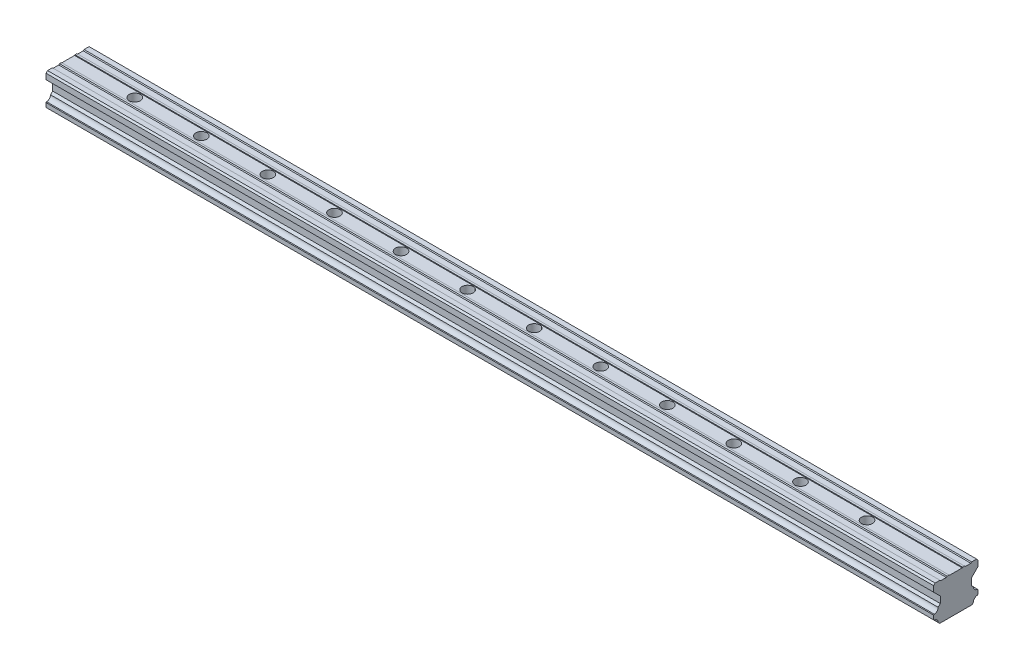
SolidWorks part; units mm, degrees
material "ASTM A36 Steel"
ref_plane "Front Plane" through (0, 0, 0) normal (0, 0, 1) x (1, 0, 0)
ref_plane "Top Plane" through (0, 0, 0) normal (0, 1, 0) x (1, 0, 0)
ref_plane "Right Plane" through (0, 0, 0) normal (1, 0, 0) x (0, 0, -1)
sketch "Sketch1" plane through (0, 0, 0) normal (1, 0, 0) x (0, 0, -1)
  line L0 (-7.9658, -7.694) -> (-7.2663, -8.3935)
  line L1 (-7.2663, -8.3935) -> (7.2663, -8.3935)
  line L2 (7.2663, -8.3935) -> (7.9658, -7.694)
  line L3 (9.7474, -5.9133) -> (10, -5.6608)
  line L4 (10, -5.6608) -> (10, -3.7884)
  line L5 (10, -3.7884) -> (9.7474, -3.5358)
  line L6 (7.9658, -1.7232) -> (7.0051, -0.7626)
  line L7 (7.0051, -0.7626) -> (7.0051, 2.1662)
  line L8 (7.0051, 2.1662) -> (10, 5.1611)
  line L9 (10, 5.1611) -> (10, 7.7124)
  line L10 (10, 7.7124) -> (9.4085, 8.3935)
  line L11 (9.4085, 8.3935) -> (7.133, 8.3935)
  line L12 (7.133, 8.3935) -> (6.7895, 8.05)
  line L13 (6.7895, 8.05) -> (4.2711, 8.05)
  line L14 (4.2711, 8.05) -> (3.9277, 8.3935)
  line L15 (3.9277, 8.3935) -> (3.0613, 8.3935)
  line L16 (3.0613, 8.3935) -> (2.872, 8.2042)
  line L17 (2.872, 8.2042) -> (-2.872, 8.2042)
  line L18 (-2.872, 8.2042) -> (-3.0613, 8.3935)
  line L19 (-3.0613, 8.3935) -> (-3.9277, 8.3935)
  line L20 (-3.9277, 8.3935) -> (-4.2712, 8.05)
  line L21 (-4.2712, 8.05) -> (-6.7895, 8.05)
  line L22 (-6.7895, 8.05) -> (-7.133, 8.3935)
  line L23 (-7.133, 8.3935) -> (-9.3077, 8.3935)
  line L24 (-9.3077, 8.3935) -> (-10, 7.7012)
  line L25 (-10, 7.7012) -> (-10, 5.1611)
  line L26 (-10, 5.1611) -> (-7.0051, 2.1662)
  line L27 (-7.0051, 2.1662) -> (-7.0051, -0.7626)
  line L28 (-7.0051, -0.7626) -> (-7.9658, -1.7232)
  line L29 (-9.7474, -5.9133) -> (-10, -5.6608)
  line L30 (-10, -5.6608) -> (-10, -3.7884)
  line L31 (-10, -3.7884) -> (-9.7474, -3.5358)
  arc A0 (-7.9658, -7.694) -> (-9.7474, -5.9133) centre (-9.7035, -7.6511) ccw
  arc A1 (-9.7474, -3.5358) -> (-7.9658, -1.7232) centre (-9.7025, -1.7981) ccw
  arc A2 (7.9658, -1.7232) -> (9.7474, -3.5358) centre (9.7025, -1.7981) ccw
  arc A3 (9.7474, -5.9133) -> (7.9658, -7.694) centre (9.7035, -7.6511) ccw
extrude "Boss-Extrude1" add sketch "Sketch1" along normal blind 400
sketch "Croquis1" plane through (0, -8.3935, 0) normal (0, -1, 0) x (1, 0, 0)
  line L0 (0, 0) -> (30, 0) construction
  line L1 (0, 7.2663) -> (0, -7.2663) construction
  circle A0 centre (30, 0) radius 2.5
  circle A1 centre (60, 0) radius 2.5
  circle A2 centre (90, 0) radius 2.5
  circle A3 centre (120, 0) radius 2.5
  circle A4 centre (150, 0) radius 2.5
  circle A5 centre (180, 0) radius 2.5
  circle A6 centre (210, 0) radius 2.5
  circle A7 centre (240, 0) radius 2.5
  circle A8 centre (270, 0) radius 2.5
  circle A9 centre (300, 0) radius 2.5
  circle A10 centre (330, 0) radius 2.5
  circle A11 centre (360, 0) radius 2.5
  dimension "D1" = 5
  dimension "D2" = 30
  dimension "D3" = 12
extrude "Cortar-Extruir1" cut sketch "Croquis1" against normal through all
